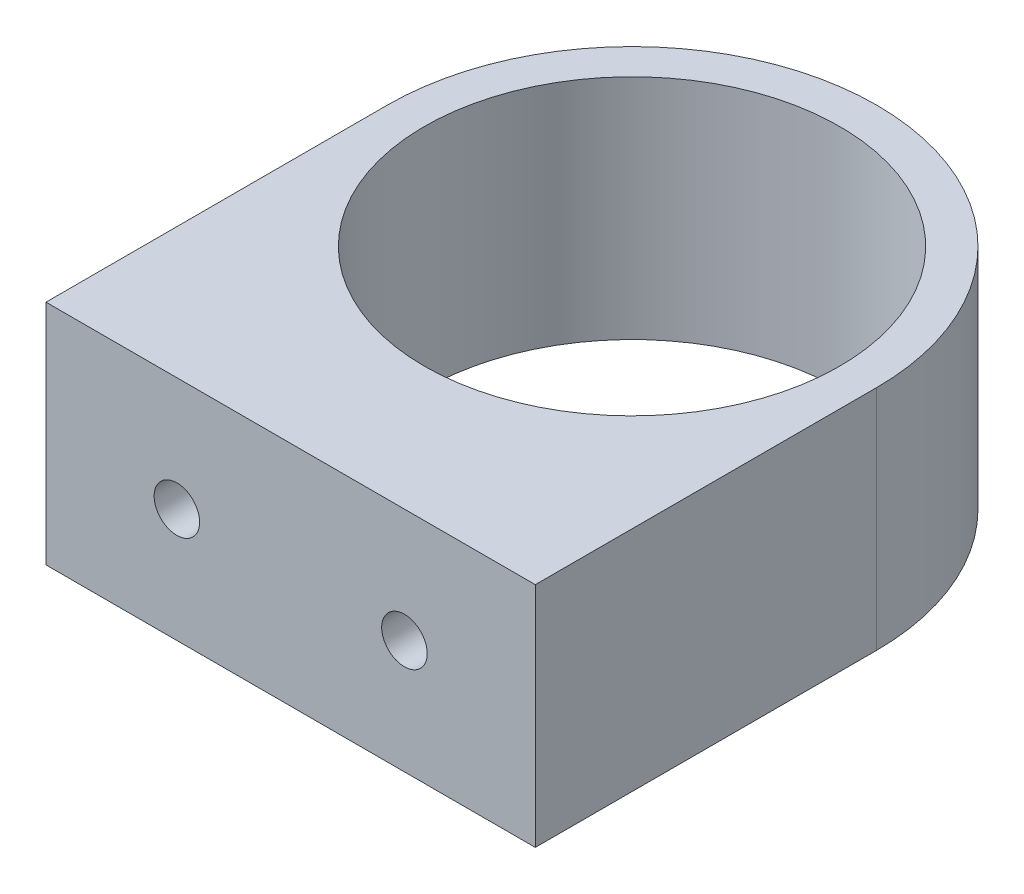
SolidWorks part; units mm, degrees
ref_plane "Front Plane" through (0, 0, 0) normal (0, 0, 1) x (1, 0, 0)
ref_plane "Top Plane" through (0, 0, 0) normal (0, 1, 0) x (1, 0, 0)
ref_plane "Right Plane" through (0, 0, 0) normal (1, 0, 0) x (0, 0, -1)
sketch "Sketch1" plane through (0, 0, 0) normal (0, 1, 0) x (1, 0, 0)
  line L0 (-21.5, 0) -> (-21.5, -30)
  line L1 (-21.5, -30) -> (21.5, -30)
  line L2 (21.5, -30) -> (21.5, 0)
  circle A0 centre (0, 0) radius 21.5
  circle A1 centre (0, 0) radius 18.25
  dimension "D1" = 43
  dimension "D3" = 36.5
  dimension "D2" = 30
extrude "Boss-Extrude1" add sketch "Sketch1" along normal blind 20 contours A0 L0 L1 L2 | A0 A1
sketch "Sketch2" plane through (0, 0, 30) normal (0, 0, 1) x (1, 0, 0)
  line L0 (-21.5, 20) -> (21.5, 20) construction
  circle A0 centre (-10, 10) radius 2
  circle A1 centre (10, 10) radius 2
  dimension "D1" = 4
  dimension "D2" = 4
  dimension "D3" = 20
  dimension "D4" = 10
  dimension "D5" = 10
  dimension "D6" = 10
extrude "Cut-Extrude1" cut sketch "Sketch2" against normal blind 10
